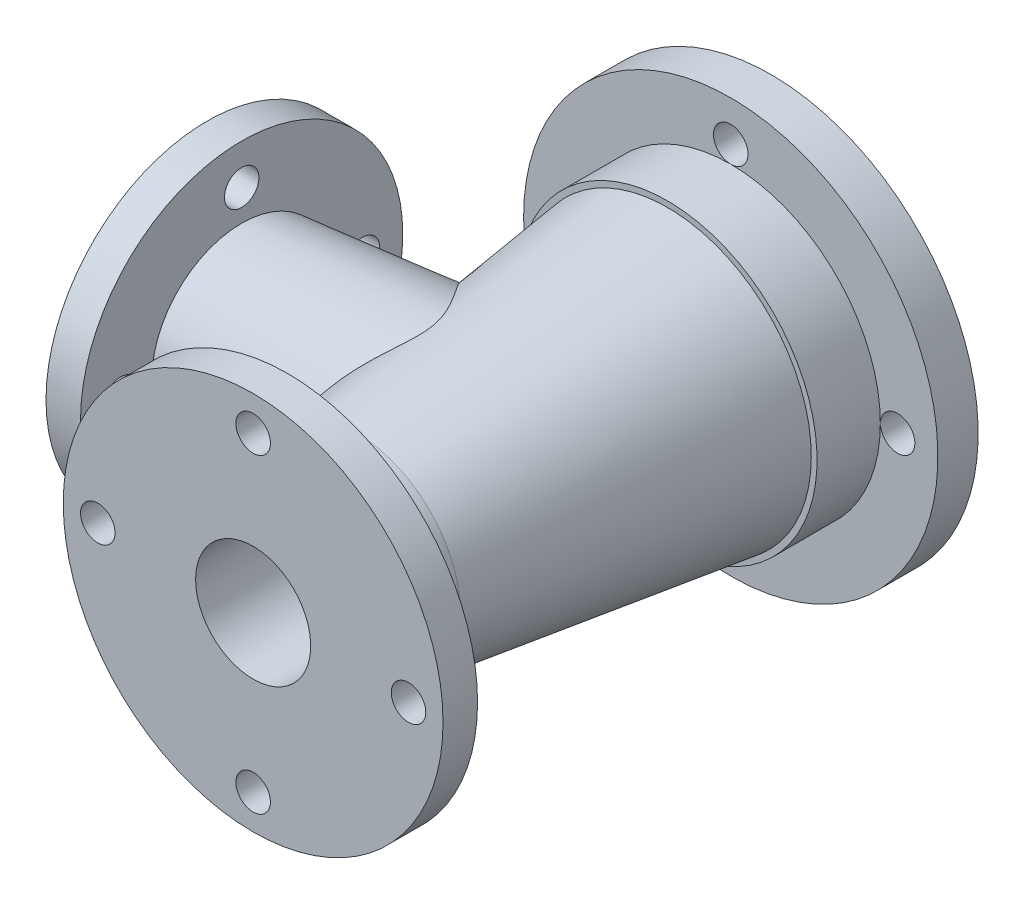
SolidWorks part; units mm, degrees
ref_plane "Front Plane" through (0, 0, 0) normal (0, 0, 1) x (1, 0, 0)
ref_plane "Top Plane" through (0, 0, 0) normal (0, 1, 0) x (1, 0, 0)
ref_plane "Right Plane" through (0, 0, 0) normal (1, 0, 0) x (0, 0, -1)
sketch "Sketch1" plane through (0, 0, 0) normal (0, 1, 0) x (1, 0, 0)
  line L0 (0, 182.98) -> (0, -106.9408) construction
  line L1 (-121.0751, 0) -> (117.3584, 0) construction
  line L2 (40, 180) -> (40, 144)
  line L3 (52, 166) -> (52, 144)
  line L4 (36, 12) -> (36, 36)
  line L5 (66, 12) -> (66, 0)
  line L6 (20, 36) -> (20, 0)
  line L7 (50, 144) -> (52, 144)
  line L8 (40, 144) -> (27, 36)
  line L9 (50, 144) -> (36, 36)
  line L10 (72, 180) -> (72, 166)
  line L11 (40, 180) -> (72, 180)
  line L12 (72, 166) -> (52, 166)
  line L14 (20, 36) -> (27, 36)
  line L15 (66, 12) -> (36, 12)
  line L16 (20, 0) -> (66, 0)
  point P7 (51, 144)
  dimension "D1" = 40
  dimension "D2" = 52
  dimension "D3" = 54
  dimension "D4" = 144
  dimension "D6" = 20
  dimension "D7" = 36
  dimension "D8" = 36
  dimension "D9" = 10
  dimension "D10" = 72
  dimension "D11" = 14
  dimension "D12" = 66
  dimension "D13" = 12
  dimension "D14" = 36
revolve "Revolve1" add sketch "Sketch1" angle 360 about L0
sketch "Sketch4" plane through (0, 0, 0) normal (0, 0, 1) x (1, 0, 0)
  line L0 (-120.8063, 0) -> (111.8639, 0) construction
  circle A0 centre (54, 0) radius 6
  circle A1 centre (0, -54) radius 6
  circle A2 centre (-54, 0) radius 6
  circle A3 centre (0, 54) radius 6
  point P14 (0, 0)
  dimension "D2" = 12
  dimension "D1" = 54
  dimension "D4" = 108
  dimension "D5" = 54
  dimension "D3" = 4
extrude "Cut-Extrude1" cut sketch "Sketch4" against normal up to surface (12 mm away) up to face at (-36, 0, -12)
sketch "Sketch5" plane through (0, 0, -180) normal (0, 0, -1) x (-1, 0, 0)
  line L0 (-104.3246, 0) -> (86.8796, 0) construction
  circle A0 centre (58, 0) radius 6
  circle A1 centre (0, -58) radius 6
  circle A2 centre (-58, 0) radius 6
  circle A3 centre (0, 58) radius 6
  point P14 (0, 0)
  dimension "D2" = 12
  dimension "D1" = 58
  dimension "D4" = 58
  dimension "D5" = 116
  dimension "D3" = 4
extrude "Cut-Extrude2" cut sketch "Sketch5" against normal up to surface (14 mm away) up to face at (-72, 0, -166)
ref_plane "Plane1" through (0, 0, -144) normal (0, 0, -1) x (-1, 0, 0)
sketch "Sketch9" plane through (0, 0, -144) normal (0, 0, -1) x (-1, 0, 0)
  circle A0 centre (0, 0) radius 40
  dimension "D1" = 80
sketch "Sketch10" plane through (0, 0, 0) normal (0, 1, 0) x (1, 0, 0)
  line L0 (0, 188.1675) -> (0, -15.2356) construction
  line L1 (26, 36) -> (0, 36)
  line L2 (-36, 36) -> (36, 36) construction
  line L4 (79.2, 144) -> (-79.2, 144) construction
  line L6 (40, 144) -> (0, 144)
  line L8 (40, 144) -> (26, 36)
  line L9 (0, 144) -> (0, 36)
  line L13 (36, 36) -> (50, 144) construction
  point P3 (50, 144)
  dimension "D1" = 10
  dimension "D2" = 10
sketch "Sketch11" plane through (0, 0, 0) normal (0, 1, 0) x (1, 0, 0)
  line L0 (0, 215.0356) -> (0, -15.5779) construction
  line L1 (0, 54.1878) -> (-100, 64)
  line L2 (-100, 64) -> (-100, 28)
  line L3 (-100, 28) -> (-88, 28)
  line L4 (-88, 28) -> (-88, 52.7745)
  line L5 (-88, 52.7745) -> (0, 44.1397)
  line L6 (-156.9303, 84) -> (165.8665, 84) construction
  line L7 (-20, 0) -> (20, 0) construction
  line L8 (-50, 144) -> (-36, 36) construction
  line L9 (0, 54.1878) -> (0, 44.1397)
  point P13 (-37.5325, 47.8225)
  point P14 (-38.8519, 58)
  dimension "D1" = 84
  dimension "D2" = 26
  dimension "D3" = 10
  dimension "D4" = 100
  dimension "D5" = 12
  dimension "D6" = 20
  dimension "D7" = 56
revolve "Revolve2" add sketch "Sketch11" angle 360 about L6
sketch "Sketch12" plane through (0, 0, 0) normal (0, 1, 0) x (1, 0, 0)
  line L0 (0, 180) -> (40, 180)
  line L1 (72, 180) -> (-72, 180) construction
  line L2 (40, 180) -> (40, 144)
  line L3 (40, 144) -> (27, 36)
  line L4 (27, 36) -> (0, 36)
  line L5 (0, 182.98) -> (0, -106.9408) construction
  line L6 (0, 36) -> (0, 180)
revolve "Cut-Revolve1" cut sketch "Sketch12" angle 360 about L0
sketch "Sketch13" plane through (0, 0, 0) normal (0, 1, 0) x (1, 0, 0)
  line L0 (-100, 64) -> (0, 54.1878)
  line L1 (0, 54.1878) -> (0, 84)
  line L2 (0, 215.0356) -> (0, -15.5779) construction
  line L3 (-156.9303, 84) -> (165.8665, 84) construction
  line L4 (0, 84) -> (-100, 84)
  line L5 (-100, 140) -> (-100, 28) construction
  line L6 (-100, 84) -> (-100, 64)
revolve "Cut-Revolve2" cut sketch "Sketch13" angle 360 about L6
sketch "Sketch14" plane through (-100, 0, 0) normal (-1, 0, 0) x (0, 0, 1)
  line L0 (-197.4346, 0) -> (29.4346, 0) construction
  line L1 (-84, 67.0157) -> (-84, -67.0157) construction
  circle A1 centre (-42, 0) radius 6
  circle A3 centre (-126, 0) radius 6
  circle A4 centre (-84, 42) radius 6
  circle A5 centre (-84, -42) radius 6
  point P0 (-84, 0)
  point P1 (-84, 0)
  dimension "D2" = 12
  dimension "D1" = 84
  dimension "D3" = 42
  dimension "D4" = 42
extrude "Cut-Extrude3" cut sketch "Sketch14" against normal up to surface (12 mm away) up to face at (-88, 0, -52.7745)
